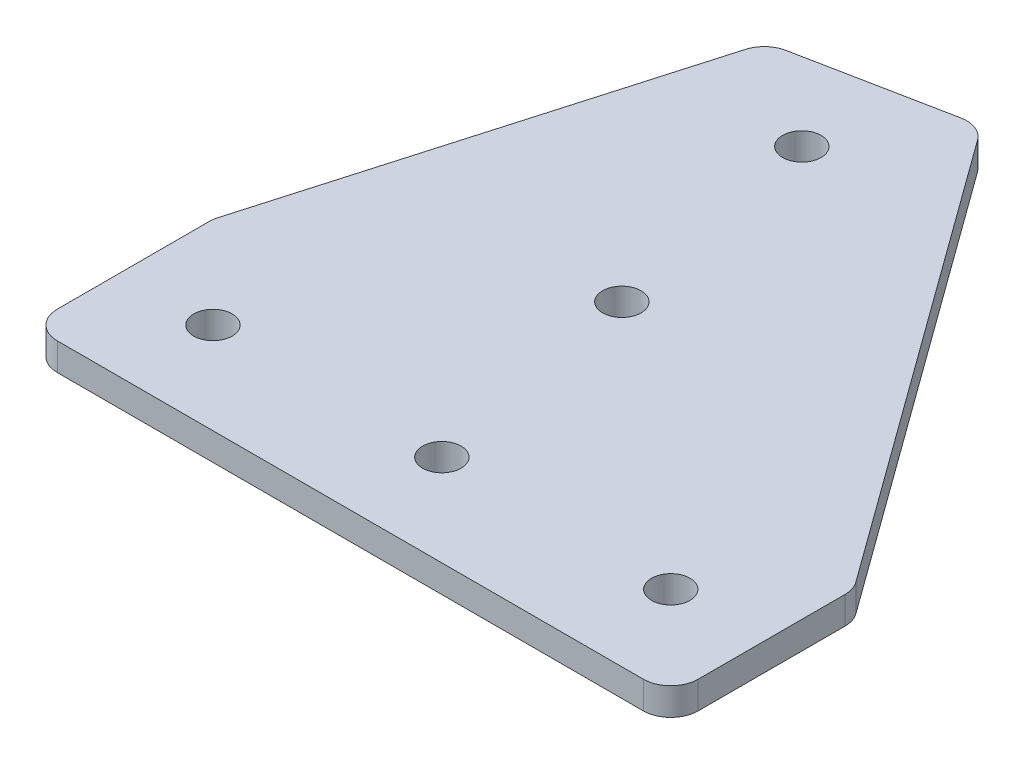
SolidWorks part; units mm, degrees
material "A-玻璃纤维"
ref_plane "前视基准面" through (0, 0, 0) normal (0, 0, 1) x (1, 0, 0)
ref_plane "上视基准面" through (0, 0, 0) normal (0, 1, 0) x (1, 0, 0)
ref_plane "右视基准面" through (0, 0, 0) normal (1, 0, 0) x (0, 0, -1)
sketch "草图1" plane through (0, 0, 0) normal (0, 1, 0) x (1, 0, 0)
  line L0 (-35, 0) -> (35, 0) construction
  line L1 (0, 0) -> (-11.6746, 58.8532) construction
  line L2 (8.2112, 10) -> (-1.8657, 60.799)
  line L3 (-35, -10) -> (35, -10)
  line L4 (9.8089, 1.9458) -> (-1.8657, 60.799) construction
  line L5 (-35, 10) -> (35, 10)
  line L6 (-12.1785, 10) -> (-21.4835, 56.9075)
  line L7 (35, 10) -> (35, -10)
  line L8 (-35, 10) -> (-35, -10)
  line L9 (-1.8657, 60.799) -> (-21.4835, 56.9075)
  line L10 (-21.4835, 56.9075) -> (-35, 10)
  line L11 (-1.8657, 60.799) -> (35, 10)
  circle A0 centre (0, 0) radius 2.1
  circle A1 centre (25, 0) radius 2.1
  circle A2 centre (-4.8644, 24.5222) radius 2.1
  circle A3 centre (-9.7288, 49.0444) radius 2.1
  circle A4 centre (-25, 0) radius 2.1
  dimension "D2" = 4.2
  dimension "D3" = 25
  dimension "D4" = 25
  dimension "D5" = 25
  dimension "D6" = 25
  dimension "D10" = 10
  dimension "D1" = 78.78
  dimension "D9" = 10
  dimension "D11" = 10
  dimension "D7" = 10
  dimension "D8" = 10
extrude "凸台-拉伸1" add sketch "草图1" along normal blind 3 contours L11 L2 L5 | L5 L8 L3 L7 A4 A1 A0 | L6 L10 L5 | L2 L9 L6 L5 A3 A2
fillet "圆角1" radius 3 6 edges at (-1.8657, 1.5, -60.799) (35, 1.5, -10) (-35, 1.5, 10) (-35, 1.5, -10) (-21.4835, 1.5, -56.9075) (35, 1.5, 10)
